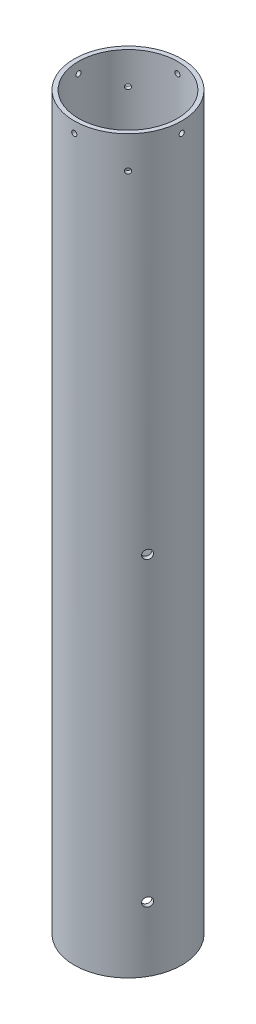
SolidWorks part; units mm, degrees
material "ПВХ 0.007 Смягченный"
ref_plane "Спереди" through (0, 0, 0) normal (0, 0, 1) x (1, 0, 0)
ref_plane "Сверху" through (0, 0, 0) normal (0, 1, 0) x (1, 0, 0)
ref_plane "Справа" through (0, 0, 0) normal (1, 0, 0) x (0, 0, -1)
sketch "Эскиз1" plane through (0, 0, 0) normal (0, 1, 0) x (1, 0, 0)
  circle A0 centre (0, 0) radius 25
  circle A1 centre (0, 0) radius 23
  dimension "ExDBody" = 50
  dimension "InDBody" = 46
extrude "Бобышка-Вытянуть1" add sketch "Эскиз1" along normal blind 340
sketch "Эскиз2" plane through (0, 0, 0) normal (1, 0, 0) x (0, 0, -1)
  line L0 (23, 340) -> (-23, 340) construction
  circle A0 centre (0, 335) radius 1.2
  dimension "D1" = 5
  dimension "D2" = 2.4
extrude "Вырез-Вытянуть1" cut sketch "Эскиз2" against normal through all
pattern_circular "Круговой массив1" count 4 over 360 about axis through (0, 340, 0) along (0, -1, 0) of "Вырез-Вытянуть1"
ref_plane "Плоскость1" through (0, 0, 0) normal (-0.7071, 0, 0.7071) x (0, -1, 0)
sketch "Эскиз3" plane through (0, 0, 0) normal (-0.7071, 0, 0.7071) x (0, -1, 0)
  line L0 (-340, 0) -> (0, 0) construction
  line L1 (-340, 25) -> (-340, -25) construction
  circle A0 centre (-325, 0) radius 1.2
  dimension "D1" = 2.4
  dimension "D2" = 15
extrude "Вырез-Вытянуть2" cut sketch "Эскиз3" against normal through all
pattern_circular "Круговой массив2" count 4 over 360 about axis through (0, 340, 0) along (0, -1, 0) of "Вырез-Вытянуть2"
sketch "Эскиз9" plane through (0, 0, 0) normal (0, 0, 1) x (1, 0, 0)
  line L0 (0, 340) -> (0, 0) construction
  circle A0 centre (0, 30) radius 2.05
  circle A1 centre (0, 170) radius 2.05
  dimension "D1" = 30
  dimension "D2" = 2
extrude "Вырез-Вытянуть6" cut sketch "Эскиз9" against normal blind 95
pattern_circular "Круговой массив3" count 3 over 360 about axis through (0, 340, 0) along (0, -1, 0) of "Вырез-Вытянуть6"
